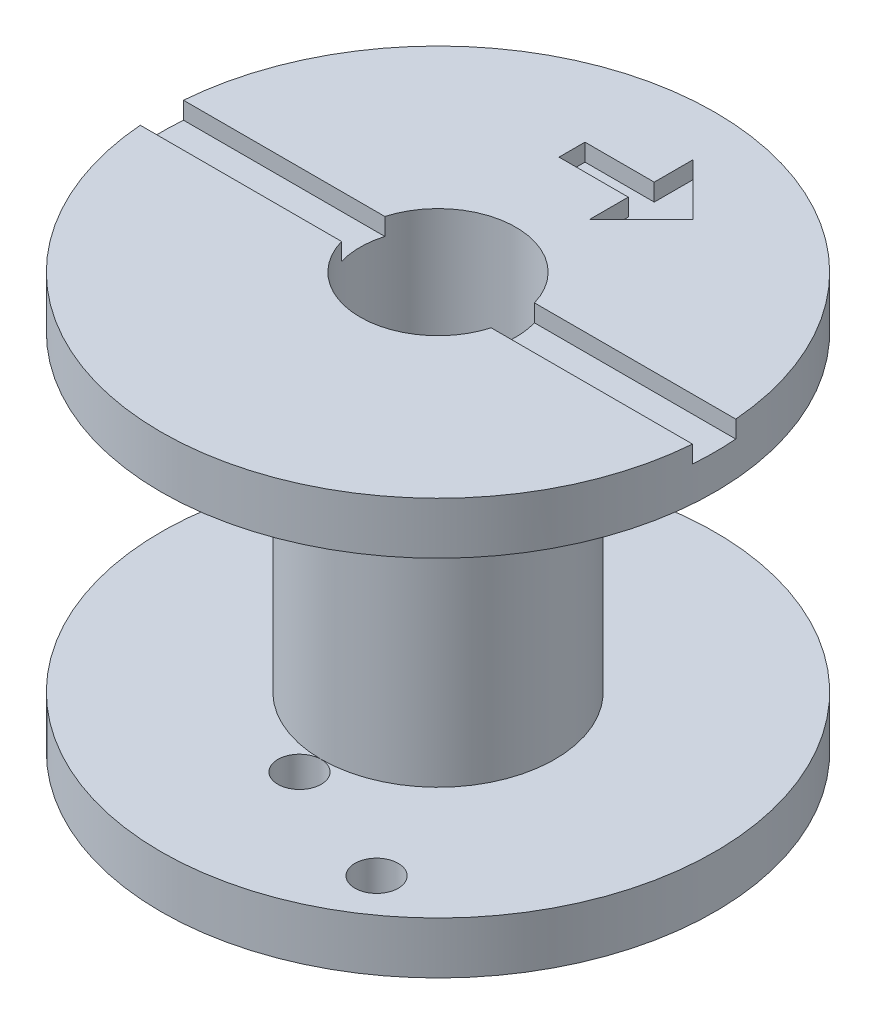
SolidWorks part; units mm, degrees
ref_plane "Front Plane" through (0, 0, 0) normal (0, 0, 1) x (1, 0, 0)
ref_plane "Top Plane" through (0, 0, 0) normal (0, 1, 0) x (1, 0, 0)
ref_plane "Right Plane" through (0, 0, 0) normal (1, 0, 0) x (0, 0, -1)
sketch "Sketch2" plane through (0, 0, 0) normal (1, 0, 0) x (0, 0, -1)
  line L0 (0, 15.5) -> (0, -9.6242) construction
  line L1 (-16, 12) -> (-16, 9)
  line L2 (-16, 9) -> (-6.75, 9)
  line L3 (-6.75, 9) -> (-6.75, -9)
  line L4 (0, 0) -> (-6.75, 0) construction
  line L5 (-16, 12) -> (-4.5, 12)
  line L6 (-16, -9) -> (-6.75, -9)
  line L7 (-16, -12) -> (-16, -9)
  line L14 (-16, -12) -> (-6.5, -12)
  line L16 (-4.5, 12) -> (-4.5, -12)
  line L17 (-6.5, -12) -> (-6.5, -14)
  line L18 (-6.5, -14) -> (-4.5, -14)
  line L19 (-4.5, -14) -> (-4.5, -12)
  point P13 (0, -15.5)
  dimension "D1" = 2
  dimension "D2" = 13.5
  dimension "D3" = 3
  dimension "D4" = 18
  dimension "D5" = 9
  dimension "D6" = 2
  dimension "D7" = 32
  dimension "D8" = 9.25
  dimension "D9" = 18
  dimension "D10" = 3
revolve "Revolve1" add sketch "Sketch2" angle 360 about L0
sketch "Sketch3" plane through (0, -12, 0) normal (0, -1, 0) x (1, 0, 0)
  circle A0 centre (0, 8) radius 1.25
  circle A1 centre (7.4254, 10.9739) radius 1.25
  dimension "D3" = 2.5
  dimension "D4" = 2.5
  dimension "D1" = 8
  dimension "D2" = 13.25
extrude "Cut-Extrude1" cut sketch "Sketch3" against normal blind 9
sketch "Sketch4" plane through (0, 12, 0) normal (0, 1, 0) x (1, 0, 0)
  line L0 (-2.2583, 10.75) -> (1.7417, 10.75)
  line L1 (1.7417, 10.75) -> (1.7417, 13)
  line L2 (1.7417, 13) -> (4.7417, 10)
  line L3 (4.7417, 10) -> (1.7417, 7)
  line L4 (1.7417, 7) -> (1.7417, 9.25)
  line L5 (1.7417, 9.25) -> (-2.2583, 9.25)
  line L6 (-2.2583, 9.25) -> (-2.2583, 10.75)
  line L7 (-2.2583, 10) -> (4.7417, 10) construction
  point P8 (-2.2583, 10)
  dimension "D1" = 1.5
  dimension "D2" = 4
  dimension "D3" = 4
  dimension "D4" = 6
  dimension "D5" = 3
  dimension "D6" = 10
extrude "Cut-Extrude2" cut sketch "Sketch4" against normal blind 1
sketch "Sketch5" plane through (0, -14, 0) normal (0, -1, 0) x (1, 0, 0)
  line L1 (21.3058, -1.25) -> (-21.3058, -1.25)
  line L2 (21.3058, -1.25) -> (21.3058, 1.25)
  line L3 (21.3058, 1.25) -> (-21.3058, 1.25)
  line L4 (-21.3058, -1.25) -> (-21.3058, 1.25)
  line L5 (21.3058, -1.25) -> (-21.3058, 1.25) construction
  line L6 (21.3058, 1.25) -> (-21.3058, -1.25) construction
  point P0 (0, 0)
  dimension "D1" = 2.5
extrude "Cut-Extrude3" cut sketch "Sketch5" along normal blind 15 and the other way blind 1 from offset 40 offset against normal yes
